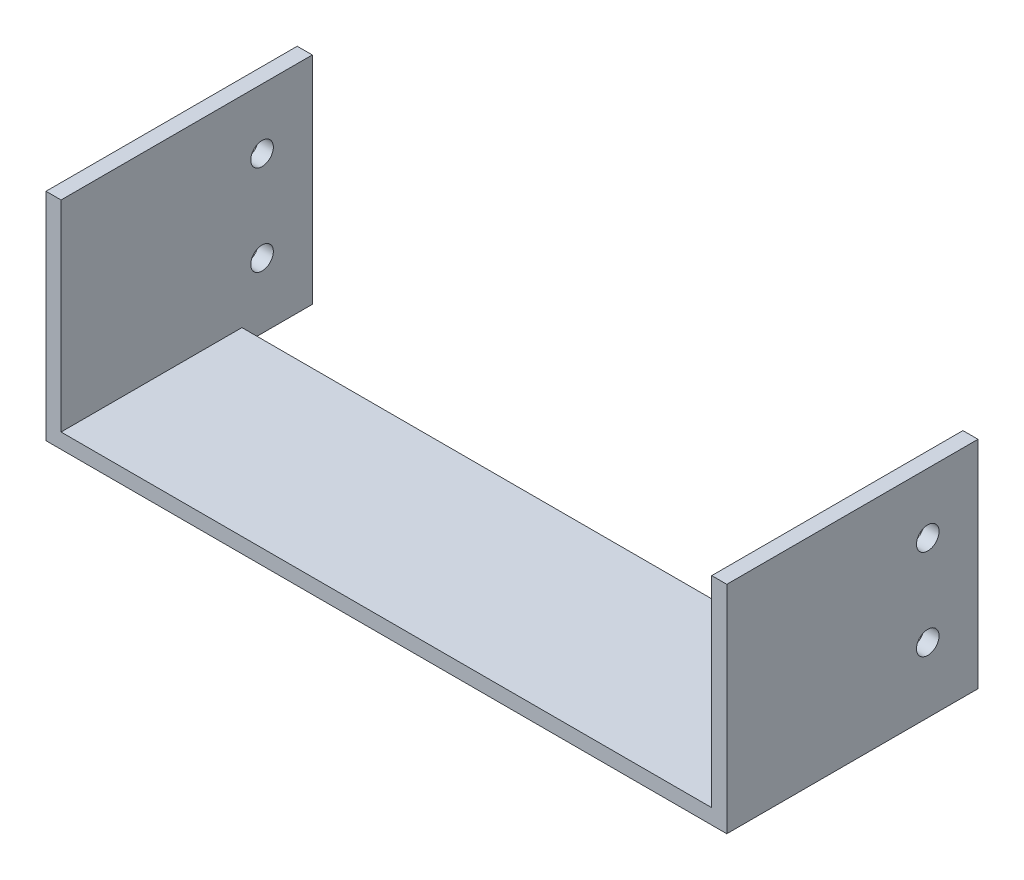
SolidWorks part; units mm, degrees
ref_plane "Front Plane" through (0, 0, 0) normal (0, 0, 1) x (1, 0, 0)
ref_plane "Top Plane" through (0, 0, 0) normal (0, 1, 0) x (1, 0, 0)
ref_plane "Right Plane" through (0, 0, 0) normal (1, 0, 0) x (0, 0, -1)
sketch "Sketch1" plane through (0, 0, 0) normal (0, 1, 0) x (1, 0, 0)
  line L0 (0, 0) -> (0, 36)
  line L1 (0, 36) -> (129.5, 36)
  line L2 (129.5, 36) -> (129.5, 0)
  line L3 (129.5, 0) -> (0, 0)
  dimension "D1" = 36
  dimension "D2" = 129.5
extrude "Boss-Extrude1" add sketch "Sketch1" along normal blind 3
ref_plane "Plane1" through (64.75, 0, 0) normal (1, 0, 0) x (0, 0, -1)
sketch "Sketch2" plane through (129.5, 0, 0) normal (1, 0, 0) x (0, 0, -1)
  line L0 (0, 0) -> (0, 43)
  line L1 (0, 43) -> (50, 43)
  line L5 (0, 3) -> (36, 3) construction
  line L6 (50, 43) -> (50, 0)
  line L7 (0, 0) -> (50, 0)
  circle A0 centre (40, 31) radius 2.25
  circle A1 centre (40, 13) radius 2.25
  dimension "D6" = 4.5
  dimension "D1" = 40
  dimension "D2" = 18
  dimension "D3" = 40
  dimension "D4" = 10
  dimension "D5" = 10
extrude "Boss-Extrude2" add sketch "Sketch2" along normal blind 3
mirror "Mirror1" about plane through (64.75, 0, 0) normal (1, 0, 0) of "Boss-Extrude2"
